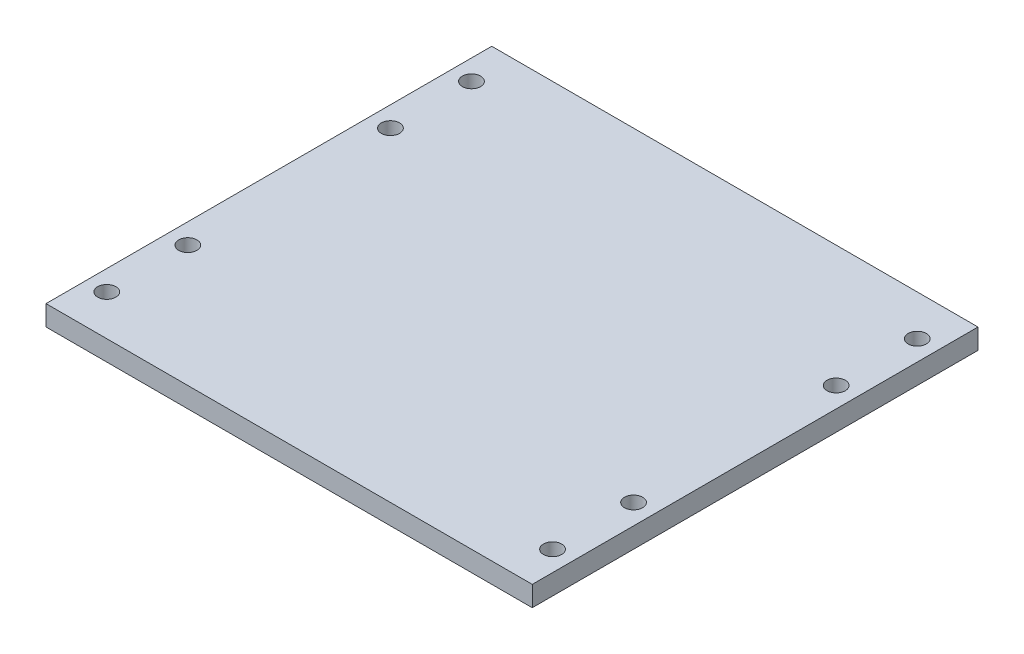
SolidWorks part; units mm, degrees
material "ALUMINIUM,  6082-T6"
ref_plane "Front Plane" through (0, 0, 0) normal (0, 0, 1) x (1, 0, 0)
ref_plane "Top Plane" through (0, 0, 0) normal (0, 1, 0) x (1, 0, 0)
ref_plane "Right Plane" through (0, 0, 0) normal (1, 0, 0) x (0, 0, -1)
sketch "Sketch1" plane through (0, 0, 0) normal (0, 1, 0) x (1, 0, 0)
  line L0 (-60, 55) -> (60, -55) construction
  line L1 (-60, 55) -> (60, 55)
  line L2 (-60, 55) -> (-60, -55)
  line L3 (-60, -55) -> (60, -55)
  line L4 (60, 55) -> (60, -55)
  dimension "D1" = 110
  dimension "D2" = 120
extrude "Boss-Extrude1" add sketch "Sketch1" along normal blind 5
hole_wizard "Ø4.5 (4.5) Diameter Hole1" positions "Sketch2" profile "Sketch3" hole size "Ø4.5" standard "ISO" end condition up to next
sketch "Sketch2" plane through (0, 5, 0) normal (0, 1, 0) x (1, 0, 0)
  line L0 (-55, 45) -> (-55, 25) construction
  line L1 (-55, 25) -> (-55, -25) construction
  line L2 (-55, -25) -> (-55, -45) construction
  line L3 (-55, -45) -> (55, -45) construction
  line L4 (55, -45) -> (55, -25) construction
  line L5 (55, -25) -> (55, 25) construction
  line L6 (55, 25) -> (55, 45) construction
  line L7 (55, 45) -> (-55, 45) construction
  line L8 (-55, 45) -> (55, -45) construction
  line L10 (-60, 55) -> (-60, -55) construction
  line L11 (60, 55) -> (-60, 55) construction
  point P0 (-55, 45)
  point P2 (-55, 25)
  point P4 (-55, -25)
  point P6 (-55, -45)
  point P8 (55, -45)
  point P10 (55, -25)
  point P12 (55, 25)
  point P14 (55, 45)
  dimension "D1" = 20
  dimension "D2" = 5
  dimension "D3" = 10
sketch "Sketch3" plane through (-55, 5, -45) normal (1, 0, 0) x (0, 0, 1)
  line L0 (0, 0) -> (0, 5)
  line L1 (0, 5) -> (2.25, 5)
  line L2 (2.25, 5) -> (2.25, 0)
  line L5 (2.25, 0) -> (0, 0)
  line L11 (0, -6.35) -> (0, 107.95) construction
  dimension "Thru Hole Dia." = 4.5
  dimension "Thru Hole Depth" = 5
